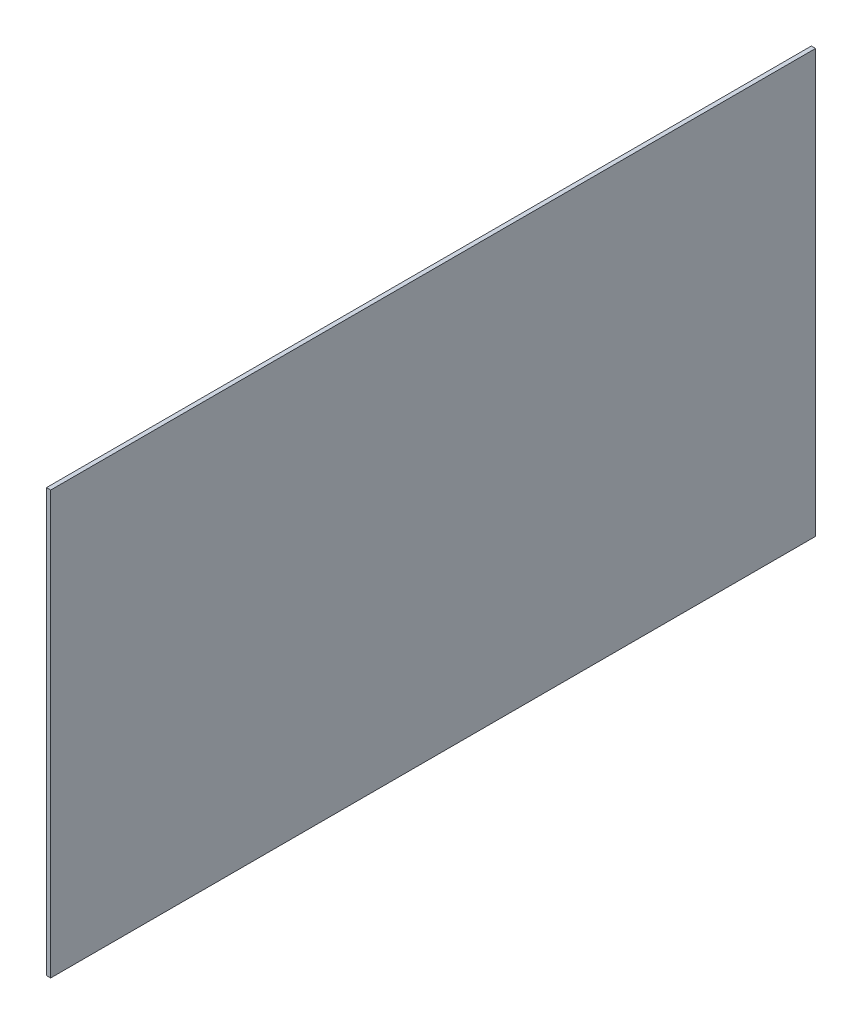
SolidWorks part; units mm, degrees
ref_plane "Front Plane" through (0, 0, 0) normal (0, 0, 1) x (1, 0, 0)
ref_plane "Top Plane" through (0, 0, 0) normal (0, 1, 0) x (1, 0, 0)
ref_plane "Right Plane" through (0, 0, 0) normal (1, 0, 0) x (0, 0, -1)
sketch "Sketch1" plane through (0, 0, 0) normal (0, 1, 0) x (1, 0, 0)
  line L5 (-1.5, 271.5) -> (1.5, 271.5)
  line L6 (-1.5, 271.5) -> (-1.5, -271.5)
  line L11 (-1.5, -271.5) -> (1.5, -271.5)
  line L12 (1.5, 271.5) -> (1.5, -271.5)
  line L13 (-1.5, 271.5) -> (1.5, -271.5) construction
  line L14 (-1.5, -271.5) -> (1.5, 271.5) construction
  point P0 (0, 0)
  dimension "D1" = 543
  dimension "D2" = 3
extrude "Boss-Extrude1" add sketch "Sketch1" along normal blind 300
